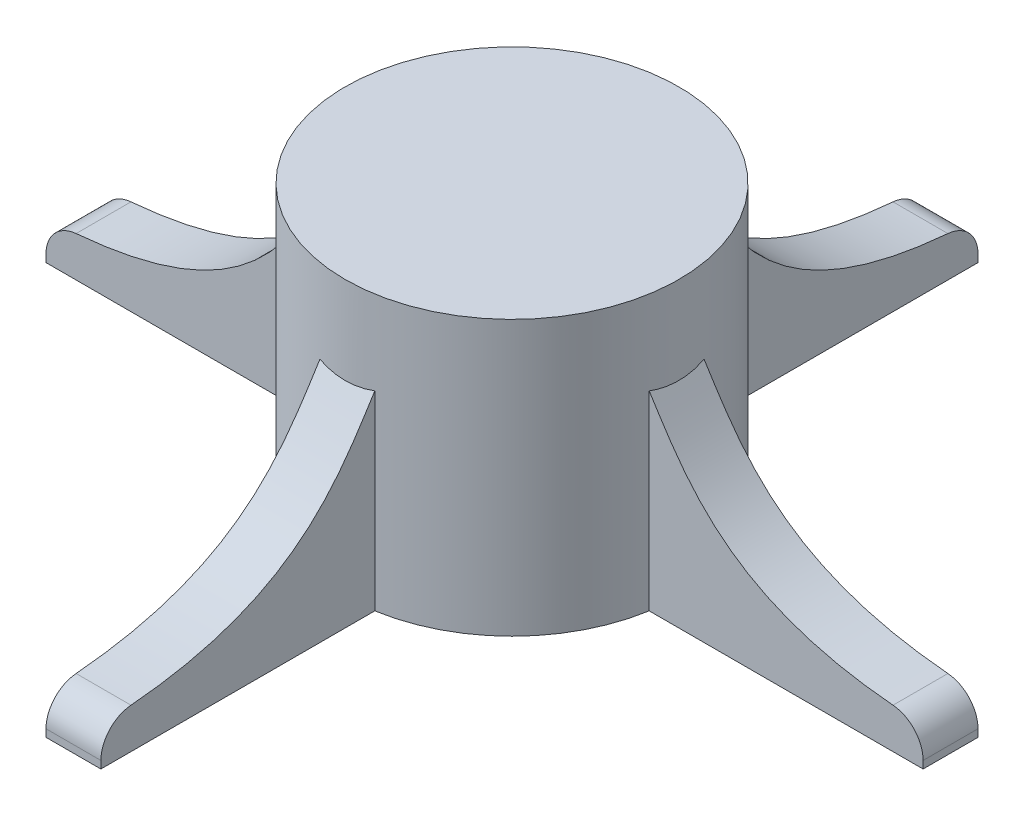
SolidWorks part; units mm, degrees
ref_plane "Front Plane" through (0, 0, 0) normal (0, 0, 1) x (1, 0, 0)
ref_plane "Top Plane" through (0, 0, 0) normal (0, 1, 0) x (1, 0, 0)
ref_plane "Right Plane" through (0, 0, 0) normal (1, 0, 0) x (0, 0, -1)
sketch "Sketch3" plane through (0, 0, 0) normal (0, 1, 0) x (1, 0, 0)
  line L1 (-15, 2.5) -> (15, 2.5)
  line L2 (-15, 2.5) -> (-15, -2.5)
  line L3 (-15, -2.5) -> (15, -2.5)
  line L4 (15, 2.5) -> (15, -2.5)
  line L5 (-15, 2.5) -> (15, -2.5) construction
  line L6 (-15, -2.5) -> (15, 2.5) construction
  line L7 (-2.5, -15) -> (2.5, -15)
  line L8 (-2.5, -15) -> (-2.5, 15)
  line L9 (-2.5, 15) -> (2.5, 15)
  line L10 (2.5, -15) -> (2.5, 15)
  line L11 (-2.5, -15) -> (2.5, 15) construction
  line L12 (-2.5, 15) -> (2.5, -15) construction
  point P0 (0, 0)
  point P6 (0, 0)
  dimension "D1" = 5
  dimension "D2" = 5
  dimension "D3" = 30
  dimension "D4" = 30
extrude "Boss-Extrude2" add sketch "Sketch3" along normal blind 25 contours L1 L10 L9 L8 | L3 L10 L1 L8 | L3 L8 L1 L2 | L10 L3 L4 L1
sketch "Sketch4" plane through (2.5, 0, 0) normal (1, 0, 0) x (0, 0, -1)
  line L0 (-2.5, 0) -> (-39.9546, 0)
  line L1 (-39.9546, 0) -> (-39.9546, 3.5)
  line L3 (-2.5, 25) -> (-2.5, 0) construction
  line L4 (-15, 17.3574) -> (-15, 25)
  line L5 (-15, 25) -> (-15, 0) construction
  line L6 (-15, 25) -> (-2.5, 25)
  line L7 (-2.5, 0) -> (-2.5, 25) construction
  line L8 (-15, 25) -> (-2.5, 25) construction
  spline S0 degree 3 poles (-39.9546, 3.5) (-10.3989, 4.5907) (-19.5926, 25.714) (-2.5, 25) knots 0 0 0 0 1 1 1 1
  point P6 (0, 0)
  point P7 (-2.5, 0)
  point P16 (-2.5, 0)
  point P17 (-2.5, 25)
  line M9 (-15, 25) -> (-15, 0)
  dimension "D2" = 37.4546
  dimension "D1" = 3.5
extrude "Cut-Extrude2" cut sketch "Sketch4" against normal through all both and the other way through all contours S0 L6 M9
sketch "Sketch5" plane through (2.5, 0, 0) normal (1, 0, 0) x (0, 0, -1)
  line L0 (-2.5, 0) -> (-39.9546, 0) construction
  line L1 (-39.9546, 0) -> (-39.9546, 3.5) construction
  line L2 (-15, 25) -> (-2.5, 25) construction
  line L4 (-2.5, 0) -> (-39.9546, 0)
  line L5 (-39.9546, 0) -> (-39.9546, 3.5)
  line L6 (-4.1276, 25) -> (-2.5, 25)
  line L7 (-2.5, 25) -> (-2.5, 0)
  line L8 (-15, 17.3574) -> (-15, 0)
  spline S0 degree 3 poles (-1817.1687, 918.2125) (1670.8433, -1068.781) (-1663.1325, 1164.0196) (1671.7026, -1068.7688) knots -2.39761 -2.39761 -2.39761 -2.39761 3.522033 3.522033 3.522033 3.522033 only from (-39.9546, 3.5) to (-2.5, 25) construction
  spline S1 degree 3 poles (-39.9546, 3.5) (-10.3989, 4.5907) (-19.5926, 25.714) (-2.5, 25) knots 0 0 0 0 1 1 1 1
  point P8 (-15, 0)
  line M7 (-15, 17.3574) -> (-15, 0)
extrude "Boss-Extrude3" add sketch "Sketch5" against normal up to surface (5 mm away) contours S1 L5 L4 M7 up to face at (-2.5, 14.2357, 6.7383)
mirror "Mirror1" about plane through (0, 0, 0) normal (0, 0, 1) of "Boss-Extrude3"
mirror "Mirror2" about plane through (0, 0, 0) normal (0, 0, 1) of "Cut-Extrude2"
sketch "Sketch9" plane through (0, 25, 0) normal (0, 1, 0) x (1, 0, 0)
  line L1 (-15, 2.5) -> (-2.5, 2.5)
  line L2 (-15, 2.5) -> (-15, -2.5)
  line L3 (-15, -2.5) -> (-2.5, -2.5)
  line L4 (-2.5, 2.5) -> (-2.5, -2.5)
  line L5 (2.5, 2.5) -> (15, 2.5)
  line L6 (2.5, 2.5) -> (2.5, -2.5)
  line L7 (2.5, -2.5) -> (15, -2.5)
  line L8 (15, 2.5) -> (15, -2.5)
extrude "Cut-Extrude3" cut sketch "Sketch9" against normal through all
pattern_circular "CirPattern9" count 4 over 360 about axis through (0, 0, 0) along (0, 1, 0) of bodies 110
ref_plane "Plane1" through (0, 0, 0) normal (-0.7071, 0, 0.7071) x (0.7071, 0, 0.7071)
sketch "Sketch11" plane through (0, 0, 0) normal (-0.7071, 0, 0.7071) x (0.7071, 0, 0.7071)
  line L0 (26.4844, 0) -> (-30.0199, 0) construction
  line L1 (-15, 25) -> (15, 25)
  line L2 (-15, 25) -> (-15, 0)
  line L3 (-15, 0) -> (15, 0)
  line L4 (15, 25) -> (15, 0)
  dimension "D1" = 30
  dimension "D2" = 25
extrude "Boss-Extrude5" add sketch "Sketch11" along normal mid plane 5
fillet "Fillet1" radius 3 4 edges at (0, 3.5, -39.9546) (39.9546, 3.5, 0) (0, 3.5, 39.9546) (-39.9546, 3.5, 0)
sketch "Sketch12" plane through (0, 25, 0) normal (0, 1, 0) x (1, 0, 0)
  circle A0 centre (0, 0) radius 15.2069
extrude "Boss-Extrude6" add sketch "Sketch12" against normal up to surface (25 mm away) up to face at (0, 0, 0)
equation "\"Length\"= 25.33"
equation "\"Width\"= 1.6"
equation "\"Tolerance\"= 0.15"
equation "\"Slot Length\"= \"Length\" + \"Tolerance\""
equation "\"Slot Width\"= \"Width\" + \"Tolerance\""
